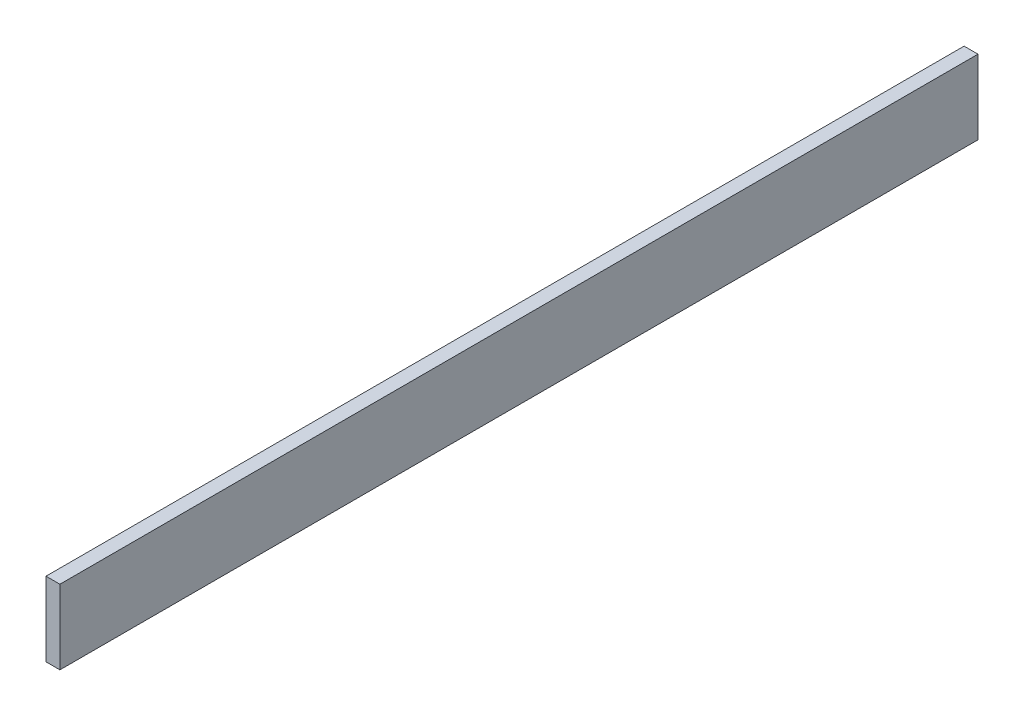
SolidWorks part; units mm, degrees
ref_plane "Front Plane" through (0, 0, 0) normal (0, 0, 1) x (1, 0, 0)
ref_plane "Top Plane" through (0, 0, 0) normal (0, 1, 0) x (1, 0, 0)
ref_plane "Right Plane" through (0, 0, 0) normal (1, 0, 0) x (0, 0, -1)
sketch "Sketch1" plane through (0, 0, 0) normal (1, 0, 0) x (0, 0, -1)
  line L1 (-628.65, -50.8) -> (628.65, -50.8)
  line L2 (-628.65, -50.8) -> (-628.65, 50.8)
  line L3 (-628.65, 50.8) -> (628.65, 50.8)
  line L4 (628.65, -50.8) -> (628.65, 50.8)
  line L5 (-628.65, -50.8) -> (628.65, 50.8) construction
  line L6 (-628.65, 50.8) -> (628.65, -50.8) construction
  point P0 (0, 0)
  dimension "D1" = 1257.3
  dimension "D2" = 101.6
extrude "Boss-Extrude1" add sketch "Sketch1" along normal blind 19.05
